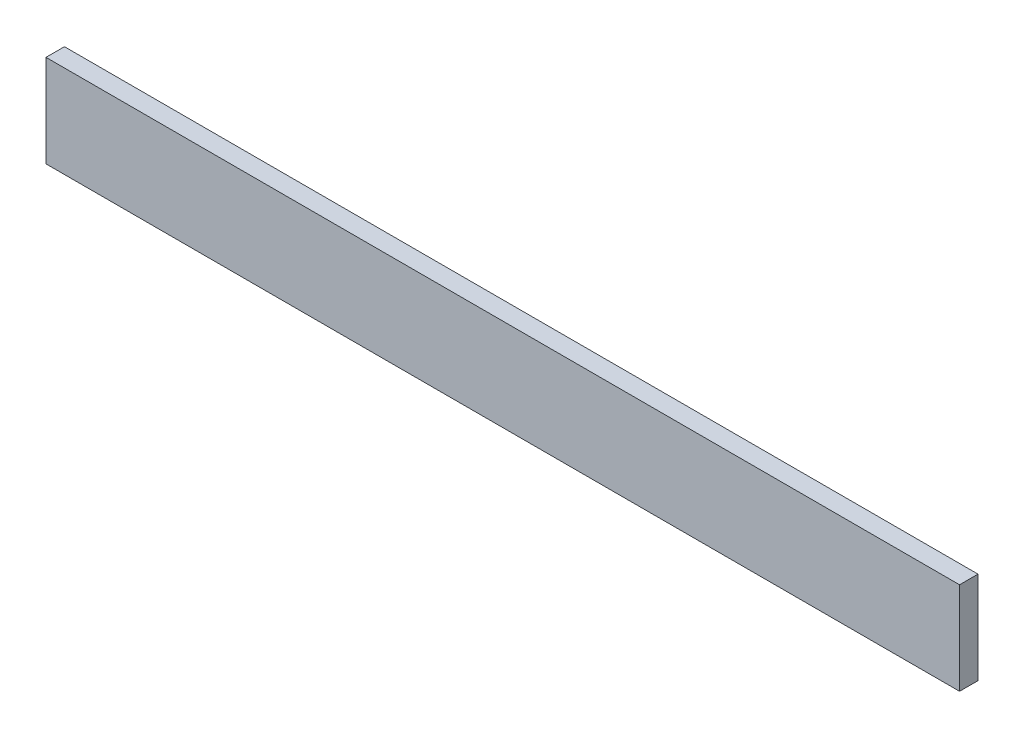
SolidWorks part; units mm, degrees
material "PLA"
ref_plane "Front Plane" through (0, 0, 0) normal (0, 0, 1) x (1, 0, 0)
ref_plane "Top Plane" through (0, 0, 0) normal (0, 1, 0) x (1, 0, 0)
ref_plane "Right Plane" through (0, 0, 0) normal (1, 0, 0) x (0, 0, -1)
sketch "Sketch1" plane through (0, 0, 0) normal (0, 0, 1) x (1, 0, 0)
  line L1 (-247.8501, 140.0283) -> (247.1499, 140.0283)
  line L2 (-247.8501, 140.0283) -> (-247.8501, 90.0283)
  line L3 (-247.8501, 90.0283) -> (247.1499, 90.0283)
  line L4 (247.1499, 140.0283) -> (247.1499, 90.0283)
  dimension "D1" = 495
  dimension "D2" = 50
extrude "Boss-Extrude1" add sketch "Sketch1" along normal blind 10
